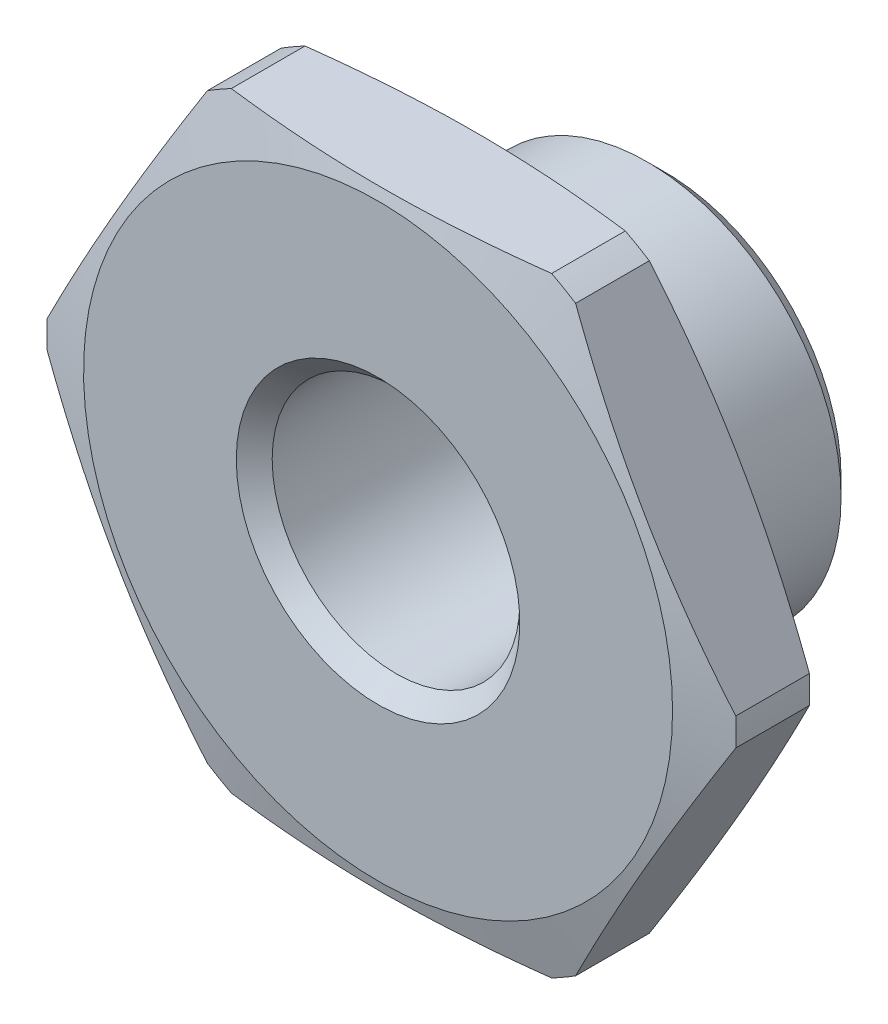
SolidWorks part; units mm, degrees
ref_plane "Front Plane" through (0, 0, 0) normal (0, 0, 1) x (1, 0, 0)
ref_plane "Top Plane" through (0, 0, 0) normal (0, 1, 0) x (1, 0, 0)
ref_plane "Right Plane" through (0, 0, 0) normal (1, 0, 0) x (0, 0, -1)
sketch "Sketch1" plane through (0, 0, 0) normal (1, 0, 0) x (0, 0, -1)
  line L0 (0, 0) -> (17.1184, 0) construction
  line L1 (0, 3.45) -> (0, 8.2054)
  line L2 (0.3737, 9.6) -> (2.4263, 9.6)
  line L3 (2.8, 8.2054) -> (2.8, 4.7)
  line L4 (2.8, 4.7) -> (4.2, 4.7)
  line L5 (4.2, 4.7) -> (4.2, 5.4)
  line L6 (4.2, 5.4) -> (7.5, 5.4)
  line L7 (7.5, 5.4) -> (8, 4.9)
  line L8 (8, 4.9) -> (8, 3.45)
  line L9 (8, 3.45) -> (0, 3.45)
  line L10 (0.3737, 9.6) -> (0, 8.2054)
  line L11 (2.4263, 9.6) -> (2.8, 8.2054)
  dimension "D1" = 10.8
  dimension "D2" = 19.2
  dimension "D3" = 8
  dimension "D4" = 9.4
  dimension "D5" = 6.9
  dimension "D6" = 5.2
  dimension "D7" = 45
  dimension "D8" = 0.5
  dimension "D9" = 3.8
  dimension "D10" = 15
  dimension "D11" = 15
  dimension "D12" = 16.4108
revolve "Revolve1" add sketch "Sketch1" angle 360 about L0
cosmetic thread "Cosmetic Thread1" parameters "D1"=3.8, "D2"=9.8
cosmetic thread "Cosmetic Thread2" parameters "D2"=7.5
sketch "Sketch2" plane through (0, 0, 0) normal (0, 0, 1) x (1, 0, 0)
  line L1 (9.815, 0) -> (4.9075, 8.5)
  line L2 (4.9075, 8.5) -> (-4.9075, 8.5)
  line L3 (-4.9075, 8.5) -> (-9.815, 0)
  line L4 (-9.815, 0) -> (-4.9075, -8.5)
  line L5 (-4.9075, -8.5) -> (4.9075, -8.5)
  line L6 (4.9075, -8.5) -> (9.815, 0)
  circle A0 centre (0, 0) radius 8.5 construction
  dimension "D1" = 17
extrude "Cut-Extrude1" cut sketch "Sketch2" against normal blind 10 flip side to cut
chamfer "Chamfer1" distance 0.5 angle 45 2 edges at (3.45, 0, 0) (3.45, 0, -8)
